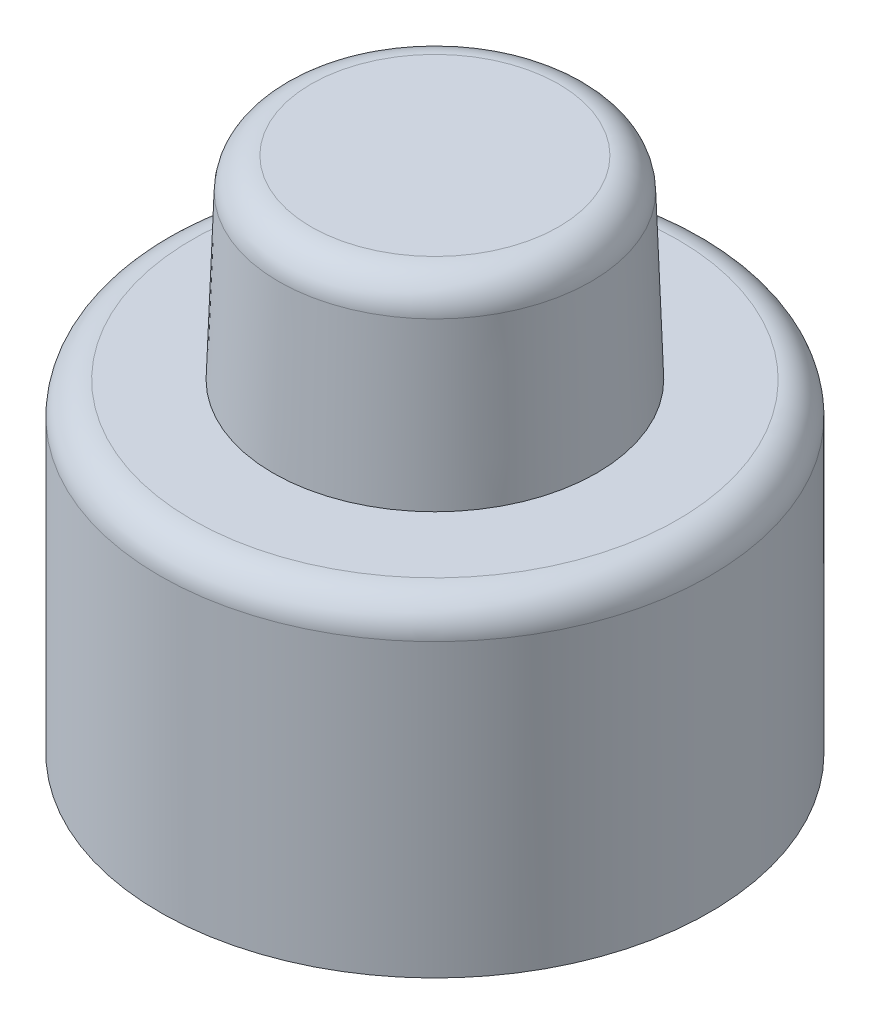
SolidWorks part; units mm, degrees
ref_plane "Front Plane" through (0, 0, 0) normal (0, 0, 1) x (1, 0, 0)
ref_plane "Top Plane" through (0, 0, 0) normal (0, 1, 0) x (1, 0, 0)
ref_plane "Right Plane" through (0, 0, 0) normal (1, 0, 0) x (0, 0, -1)
sketch "Sketch1" plane through (0, 0, 0) normal (0, 1, 0) x (1, 0, 0)
  circle A0 centre (-51.1202, 0) radius 8.5
extrude "Boss-Extrude1" add sketch "Sketch1" along normal blind 6
sketch "Sketch2" plane through (0, 6, 0) normal (0, 1, 0) x (1, 0, 0)
  circle A0 centre (-51.1202, 0) radius 5
  circle A1 centre (-51.1202, 0) radius 8.5 construction
fillet "Fillet2" radius 1 1 edges at (-51.1202, 6, 8.5)
extrude "Boss-Extrude3" add sketch "Sketch2" along normal blind 6 draft 2 contours A0
fillet "Fillet4" radius 1 1 edges at (-51.1202, 12, 4.7905)
sketch "Sketch3" plane through (0, 0, 0) normal (0, -1, 0) x (1, 0, 0)
  line L0 (-59.6202, 0) -> (-42.6202, 0) construction
  line L1 (-59.6202, 0) -> (-51.6202, 0)
  line L2 (-59.6202, 0) -> (70.3798, 0)
  line L3 (-59.6202, 0) -> (-46.6165, 0)
  line L4 (-46.6165, 0) -> (-46.6165, -7.2088)
  line L5 (-51.6202, 0) -> (-51.6202, -8.4853)
  line L7 (-51.6202, -8.4853) -> (-46.6165, -8.4853)
  line L8 (-51.6202, -8.4853) -> (-51.6202, 1.5147)
  line L9 (-51.6202, 1.5147) -> (-46.6165, 1.5147)
  line L10 (-46.6165, -8.4853) -> (-46.6165, 1.5147)
  circle A0 centre (-51.1202, 0) radius 8.5 construction
  circle M8 centre (-51.1202, 0) radius 8.5
extrude "Boss-Extrude4" add sketch "Sketch3" along normal blind 4 contours L5 L1 M8 | L10 L2 L1 L8 L9 M8 | L2 L4 M8
sketch "Sketch6" plane through (0, -4, 0) normal (0, -1, 0) x (1, 0, 0)
  line L1 (-51.6202, 1.5147) -> (-46.6165, 1.5147)
  line L2 (-51.6202, 1.5147) -> (-51.6202, -8.7002)
  line L3 (-51.6202, -8.7002) -> (-46.6165, -8.7002)
  line L4 (-46.6165, 1.5147) -> (-46.6165, -8.7002)
  arc A0 (-46.6165, -7.2088) -> (-51.6202, -8.4853) centre (-51.1202, 0) cw
  line M1 (-51.6202, -8.4853) -> (-51.6202, 1.5147)
  line M2 (-51.6202, 1.5147) -> (-46.6165, 1.5147)
  line M3 (-46.6165, 1.5147) -> (-46.6165, -7.2088)
extrude "Cut-Extrude4" cut sketch "Sketch6" against normal blind 7 contours A0 M3 M2 M1
equation "\".5.00mm\"=1"
